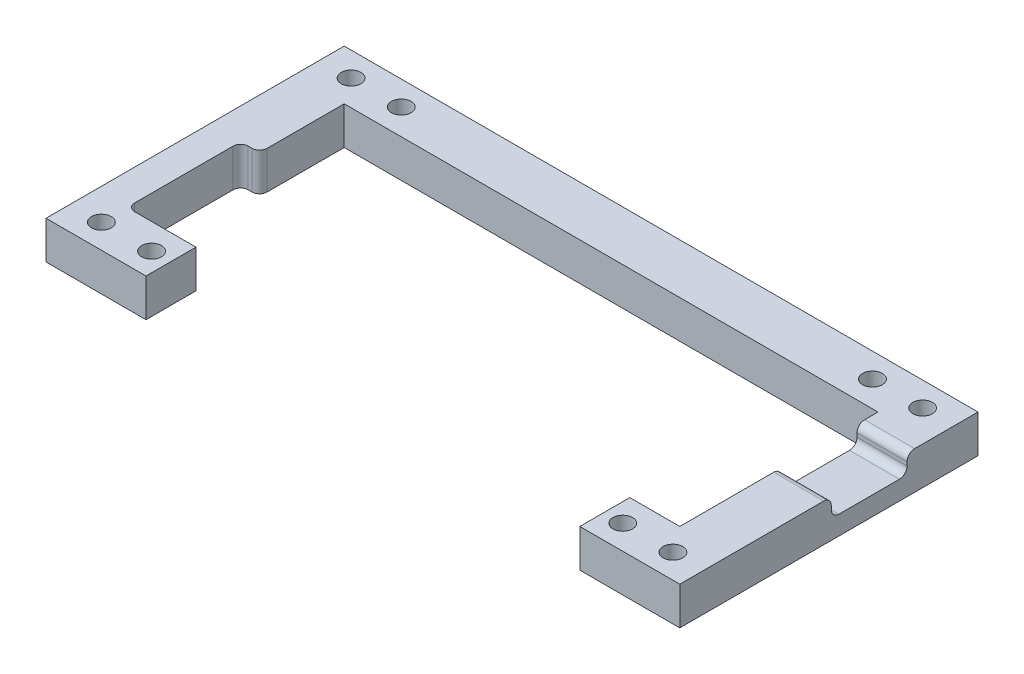
SolidWorks part; units mm, degrees
ref_plane "Front Plane" through (0, 0, 0) normal (0, 0, 1) x (1, 0, 0)
ref_plane "Top Plane" through (0, 0, 0) normal (0, 1, 0) x (1, 0, 0)
ref_plane "Right Plane" through (0, 0, 0) normal (1, 0, 0) x (0, 0, -1)
sketch "Sketch1" plane through (0, 0, 0) normal (0, 1, 0) x (1, 0, 0)
  line L0 (181.4198, 36.9979) -> (75.1552, 36.9979) construction
  line L1 (75.1552, 11.9979) -> (83.5372, 11.9979)
  line L2 (75.1552, 11.9979) -> (75.1552, 61.9979)
  line L3 (75.1552, 61.9979) -> (83.5372, 61.9979)
  line L4 (83.5372, 11.9979) -> (83.5372, 61.9979)
  line L5 (83.5372, 61.9979) -> (91.9192, 61.9979)
  line L6 (83.5372, 61.9979) -> (83.5372, 53.6159)
  line L7 (83.5372, 53.6159) -> (91.9192, 53.6159)
  line L8 (167.7876, 16.0648) -> (186.7138, 16.0648) construction
  line L9 (83.5372, 11.9979) -> (91.9192, 11.9979)
  line L10 (83.5372, 11.9979) -> (83.5372, 20.3799)
  line L11 (83.5372, 20.3799) -> (91.9192, 20.3799)
  line L12 (91.9192, 11.9979) -> (91.9192, 20.3799)
  line L13 (75.1552, 61.9979) -> (181.4198, 61.9979)
  line L17 (181.4198, 61.9979) -> (173.0378, 61.9979)
  line L18 (181.4198, 61.9979) -> (181.4198, 11.9979)
  line L19 (181.4198, 11.9979) -> (173.0378, 11.9979)
  line L20 (173.0378, 61.9979) -> (173.0378, 11.9979)
  line L21 (173.0378, 61.9979) -> (164.6558, 61.9979)
  line L22 (173.0378, 61.9979) -> (173.0378, 53.6159)
  line L23 (173.0378, 53.6159) -> (164.6558, 53.6159)
  line L25 (173.0378, 11.9979) -> (164.6558, 11.9979)
  line L26 (173.0378, 11.9979) -> (173.0378, 20.3799)
  line L27 (173.0378, 20.3799) -> (164.6558, 20.3799)
  line L28 (164.6558, 11.9979) -> (164.6558, 20.3799)
  line L29 (128.2875, 61.9979) -> (128.2875, -9.1774) construction
  line L30 (164.6558, 53.6159) -> (91.9192, 53.6159)
  circle A0 centre (167.7876, 57.931) radius 1.651
  circle A1 centre (167.7876, 16.0648) radius 1.651
  circle A2 centre (88.7875, 16.0648) radius 1.651
  circle A3 centre (88.7875, 57.931) radius 1.651
  circle A4 centre (176.2028, 16.0648) radius 1.651
  circle A5 centre (80.3722, 16.0648) radius 1.651
  circle A6 centre (80.3722, 57.931) radius 1.651
  circle A7 centre (176.2028, 57.931) radius 1.651
  point P32 (91.9192, 16.1889)
  point P34 (88.7875, 57.931)
  point P35 (88.7875, 16.0648)
  dimension "D15" = 3.302
  dimension "D16" = 3.1342
  dimension "D6" = 79.0001
  dimension "D18" = 3.302
  dimension "D2" = 47.9153
  dimension "D1" = 8.382
  dimension "D3" = 50
  dimension "D4" = 8.382
  dimension "D5" = 50
  dimension "D7" = 8.382
  dimension "D8" = 8.382
  dimension "D9" = 8.382
  dimension "D10" = 8.382
  dimension "D11" = 8.382
  dimension "D12" = 8.382
  dimension "D13" = 8.382
  dimension "D14" = 8.382
  dimension "D17" = 3.1317
extrude "Boss-Extrude1" add sketch "Sketch1" along normal blind 6.35
sketch "Sketch2" plane through (181.4198, 0, 0) normal (1, 0, 0) x (0, 0, -1)
  line L0 (61.9979, 6.35) -> (11.9979, 6.35) construction
  line L1 (37.3979, 6.35) -> (50.0979, 6.35)
  line L2 (37.3979, 6.35) -> (37.3979, 3.175)
  line L3 (37.3979, 3.175) -> (50.0979, 3.175)
  line L4 (50.0979, 6.35) -> (50.0979, 3.175)
  line L5 (11.9979, 6.35) -> (11.9979, 0) construction
  dimension "D1" = 25.4
  dimension "D2" = 12.7
  dimension "D3" = 3.175
extrude "Cut-Extrude7" cut sketch "Sketch2" against normal blind 8.89 contours L2 L3 L4 L1
fillet "Fillet2" radius 1.27 4 edges at (177.2288, 3.175, -37.3979) (177.2288, 6.35, -37.3979) (177.2288, 3.175, -50.0979) (177.2288, 6.35, -50.0979)
sketch "Sketch4" plane through (0, 6.35, 0) normal (0, 1, 0) x (1, 0, 0)
  line L1 (83.5372, 20.3799) -> (80.3622, 20.3799)
  line L2 (83.5372, 20.3799) -> (83.5372, 39.4299)
  line L3 (83.5372, 39.4299) -> (80.3622, 39.4299)
  line L4 (80.3622, 20.3799) -> (80.3622, 39.4299)
  dimension "D1" = 3.175
  dimension "D2" = 19.05
extrude "Cut-Extrude8" cut sketch "Sketch4" against normal through all
fillet "Fillet3" radius 1.27 3 edges at (80.3622, 3.175, -20.3799) (80.3622, 3.175, -39.4299) (83.5372, 3.175, -39.4299)
sketch "Sketch5" plane through (0, 0, 0) normal (0, -1, 0) x (1, 0, 0)
  circle A0 centre (88.7875, -16.0648) radius 2.8575
  circle A1 centre (88.7875, -57.931) radius 3.175
  circle A2 centre (167.7876, -57.931) radius 3.175
  circle A3 centre (167.7876, -16.0648) radius 2.8575
  dimension "D1" = 5.715
  dimension "D2" = 6.35
  dimension "D3" = 5.715
  dimension "D4" = 6.35
extrude "Cut-Extrude9" cut sketch "Sketch5" against normal blind 2.54
